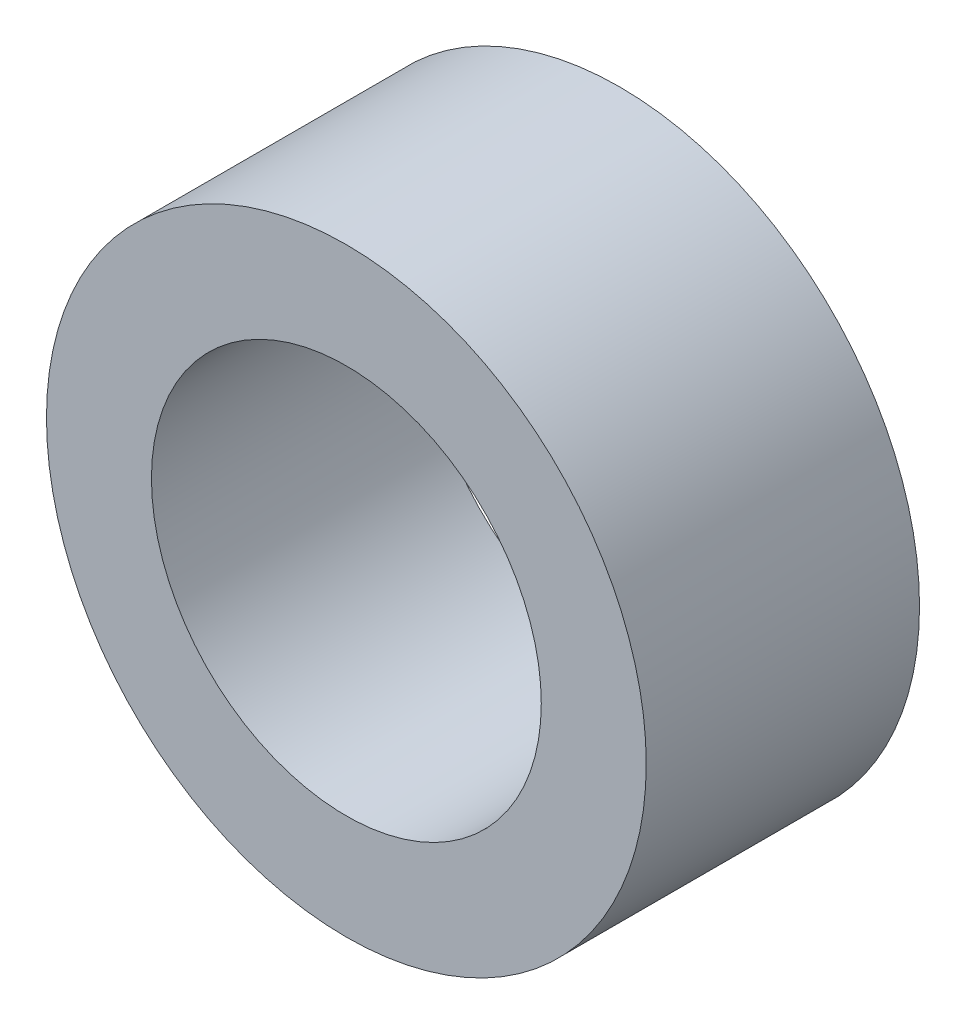
SolidWorks part; units mm, degrees
material "Brass"
ref_plane "Front Plane" through (0, 0, 0) normal (0, 0, 1) x (1, 0, 0)
ref_plane "Top Plane" through (0, 0, 0) normal (0, 1, 0) x (1, 0, 0)
ref_plane "Right Plane" through (0, 0, 0) normal (1, 0, 0) x (0, 0, -1)
sketch "Sketch1" plane through (0, 0, 0) normal (0, 0, 1) x (1, 0, 0)
  circle A0 centre (0, 0) radius 5
  circle A1 centre (0, 0) radius 3.25
  dimension "D1" = 10
  dimension "D2" = 6.5
extrude "Boss-Extrude1" add sketch "Sketch1" along normal mid plane 4.5565
